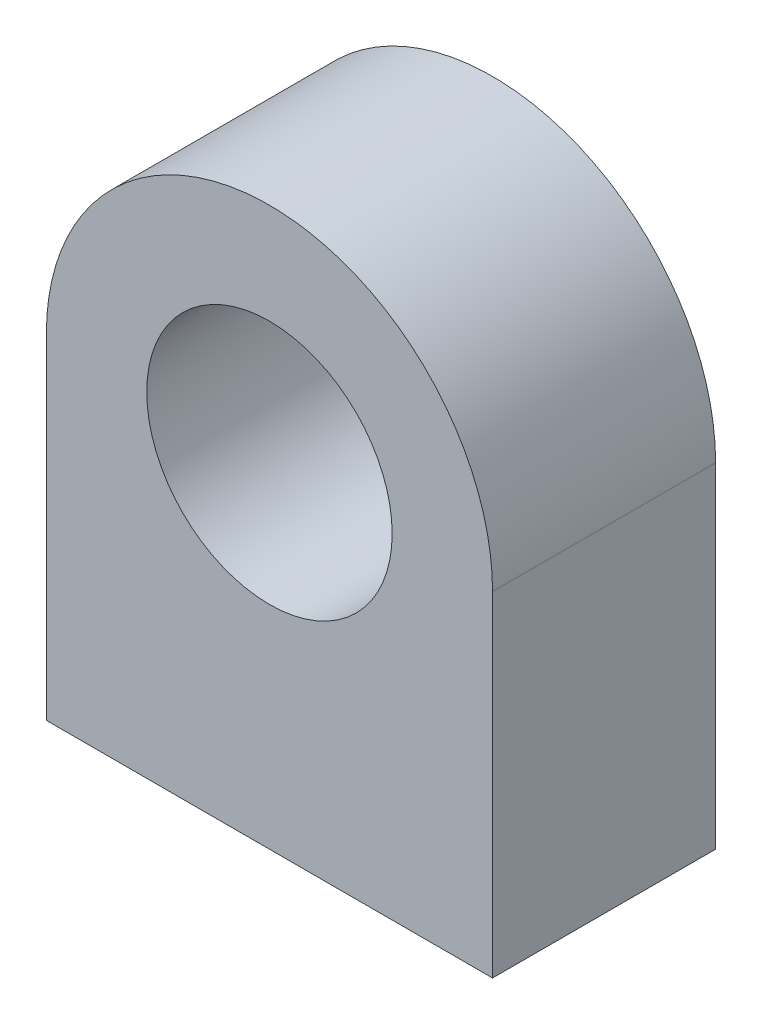
SolidWorks part; units mm, degrees
ref_plane "Front Plane" through (0, 0, 0) normal (0, 0, 1) x (1, 0, 0)
ref_plane "Top Plane" through (0, 0, 0) normal (0, 1, 0) x (1, 0, 0)
ref_plane "Right Plane" through (0, 0, 0) normal (1, 0, 0) x (0, 0, -1)
sketch "Sketch1" plane through (0, 0, 0) normal (0, 0, 1) x (1, 0, 0)
  line L2 (-10, 0) -> (-10, -15)
  line L3 (-10, -15) -> (10, -15)
  line L4 (10, 0) -> (10, -15)
  circle A0 centre (0, 0) radius 5.5
  arc A1 (10, 0) -> (-10, 0) centre (0, 0) ccw
  dimension "D1" = 11
  dimension "D2" = 20
  dimension "D3" = 15
extrude "Boss-Extrude1" add sketch "Sketch1" along normal blind 10
